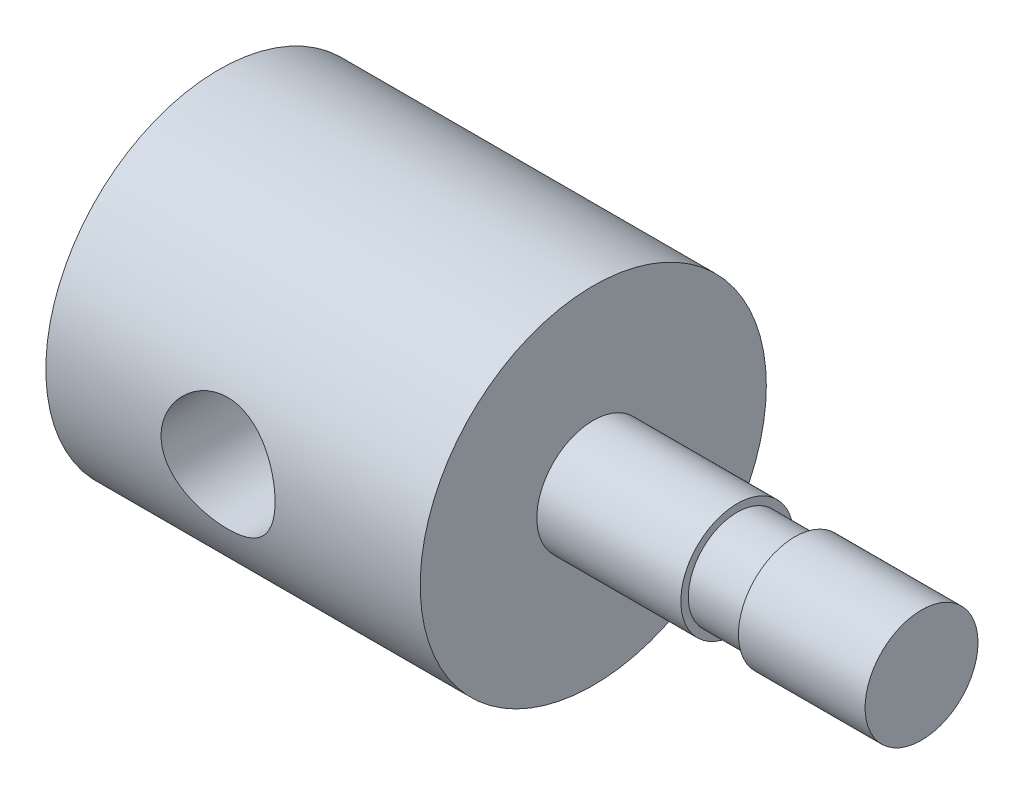
SolidWorks part; units mm, degrees
ref_plane "Piano frontale" through (0, 0, 0) normal (0, 0, 1) x (1, 0, 0)
ref_plane "Piano superiore" through (0, 0, 0) normal (0, 1, 0) x (1, 0, 0)
ref_plane "Piano destro" through (0, 0, 0) normal (1, 0, 0) x (0, 0, -1)
sketch "Schizzo1" plane through (0, 0, 0) normal (1, 0, 0) x (0, 0, -1)
  circle A0 centre (0, 0) radius 3.005
  dimension "D1" = 6.01
extrude "Estrusione-Estrusione1" add sketch "Schizzo1" along normal blind 6.5
sketch "Schizzo2" plane through (6.5, 0, 0) normal (1, 0, 0) x (0, 0, -1)
  circle A0 centre (0, 0) radius 0.98
  dimension "D1" = 1.96
extrude "Estrusione-Estrusione2" add sketch "Schizzo2" along normal blind 2.5
sketch "Schizzo3" plane through (9, 0, 0) normal (1, 0, 0) x (0, 0, -1)
  circle A0 centre (0, 0) radius 0.85
  dimension "D1" = 1.7
extrude "Estrusione-Estrusione3" add sketch "Schizzo3" along normal blind 1
sketch "Schizzo4" plane through (10, 0, 0) normal (1, 0, 0) x (0, 0, -1)
  circle A0 centre (0, 0) radius 0.98 construction
  circle A1 centre (0, 0) radius 0.98
extrude "Estrusione-Estrusione4" add sketch "Schizzo4" along normal blind 2.2
hole_wizard "Foro filettato M3x0.5-1" positions "Schizzo6" profile "Schizzo5" tap size "M3x0.5" standard "Ansi Metric"
sketch "Schizzo6" plane through (0, 0, 0) normal (-1, 0, 0) x (0, 0, 1)
  point P0 (0, 0)
sketch "Schizzo5" plane through (0, 0, 0) normal (0, 1, 0) x (0, 0, 1)
  line L0 (0, 0) -> (0, 5.7511)
  line L1 (0, 5.7511) -> (1.25, 5)
  line L2 (1.25, 5) -> (1.25, 0)
  line L5 (1.25, 0) -> (0, 0)
  line L10 (0, 5.7511) -> (-1.25, 5) construction
  line L11 (0, -6.35) -> (0, 107.95) construction
  dimension "Tap Drill Dia." = 2.5
  dimension "Tap Drill Depth" = 5
  dimension "Drill Angle" = 118
cosmetic thread "Filettatura del foro1" parameters "D1"=5, "D2"=3
sketch "Schizzo7" plane through (0, 0, 0) normal (0, 0, 1) x (1, 0, 0)
  line L0 (0, 3.005) -> (0, -3.005) construction
  circle A0 centre (2.99, 0) radius 0.99
  point P2 (2, 0)
  dimension "D1" = 1.98
  dimension "D2" = 2
extrude "Taglio-Estrusione1" cut sketch "Schizzo7" against normal through all and the other way through all
